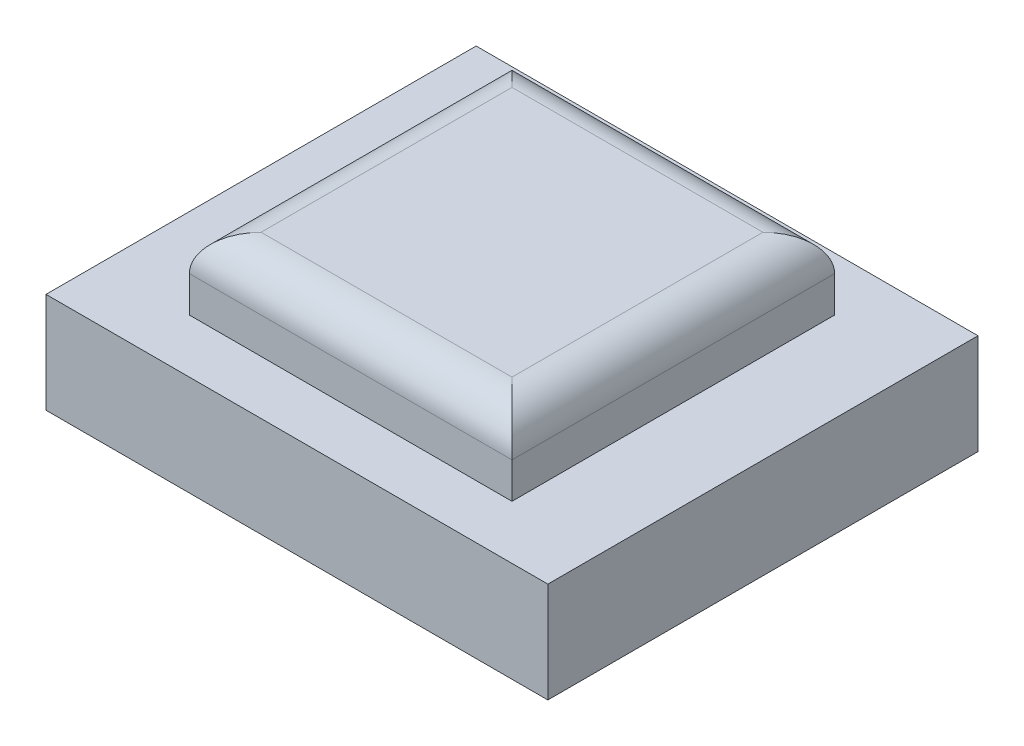
SolidWorks part; units mm, degrees
ref_plane "Front Plane" through (0, 0, 0) normal (0, 0, 1) x (1, 0, 0)
ref_plane "Top Plane" through (0, 0, 0) normal (0, 1, 0) x (1, 0, 0)
ref_plane "Right Plane" through (0, 0, 0) normal (1, 0, 0) x (0, 0, -1)
sketch "Sketch1" plane through (0, 0, 0) normal (0, 1, 0) x (1, 0, 0)
  line L1 (-1.75, 1.5) -> (1.75, 1.5)
  line L2 (-1.75, 1.5) -> (-1.75, -1.5)
  line L3 (-1.75, -1.5) -> (1.75, -1.5)
  line L4 (1.75, 1.5) -> (1.75, -1.5)
  line L5 (-1.75, 1.5) -> (1.75, -1.5) construction
  line L6 (-1.75, -1.5) -> (1.75, 1.5) construction
  point P0 (0, 0)
  dimension "D1" = 3.5
  dimension "D2" = 3
extrude "Boss-Extrude1" add sketch "Sketch1" along normal blind 0.7
sketch "Sketch2" plane through (0, 0.7, 0) normal (0, 1, 0) x (1, 0, 0)
  line L1 (-1.125, 1.125) -> (1.125, 1.125)
  line L2 (-1.125, 1.125) -> (-1.125, -1.125)
  line L3 (-1.125, -1.125) -> (1.125, -1.125)
  line L4 (1.125, 1.125) -> (1.125, -1.125)
  line L5 (-1.125, 1.125) -> (1.125, -1.125) construction
  line L6 (-1.125, -1.125) -> (1.125, 1.125) construction
  point P0 (0, 0)
  dimension "D1" = 2.25
  dimension "D2" = 2.25
extrude "Boss-Extrude2" add sketch "Sketch2" along normal blind 0.5 contours L4 L3 L2 L1
fillet "Fillet1" radius 0.25 4 edges at (0, 1.2, 1.125) (-1.125, 1.2, 0) (0, 1.2, -1.125) (1.125, 1.2, 0)
